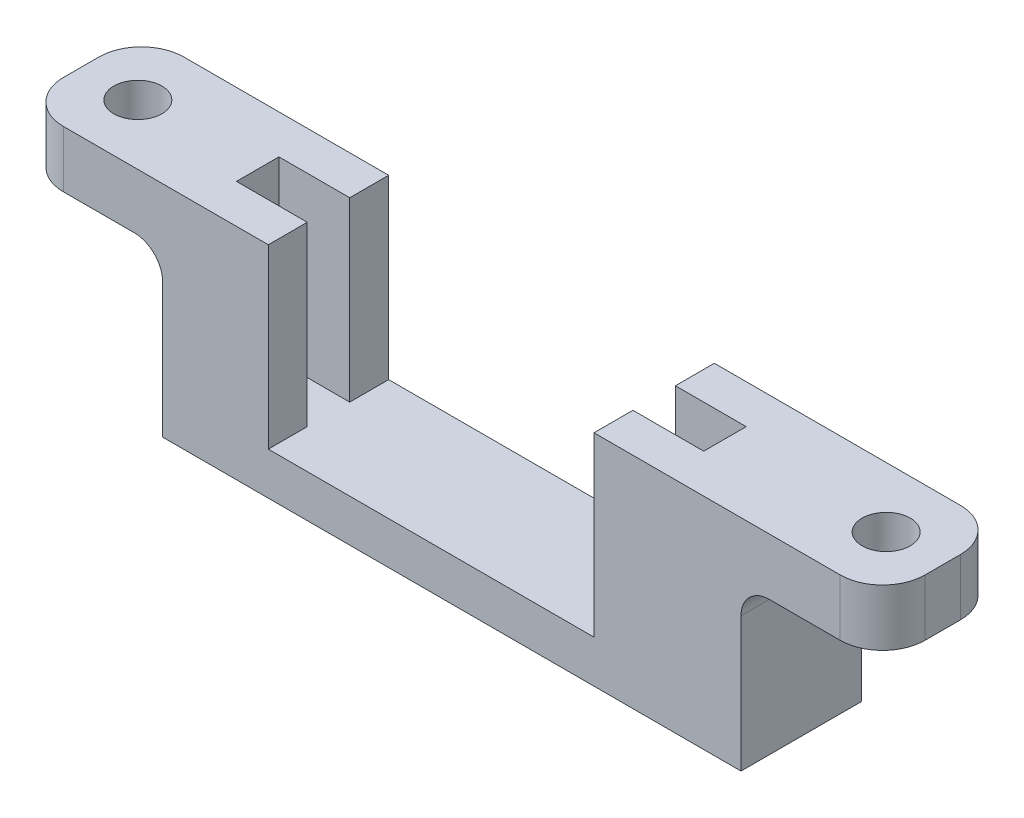
SolidWorks part; units mm, degrees
ref_plane "Front Plane" through (0, 0, 0) normal (0, 0, 1) x (1, 0, 0)
ref_plane "Top Plane" through (0, 0, 0) normal (0, 1, 0) x (1, 0, 0)
ref_plane "Right Plane" through (0, 0, 0) normal (1, 0, 0) x (0, 0, -1)
sketch "Sketch1" plane through (0, 0, 0) normal (0, 1, 0) x (1, 0, 0)
  line L1 (-30.425, 4.25) -> (30.425, 4.25)
  line L2 (-30.425, 4.25) -> (-30.425, -4.25)
  line L3 (-30.425, -4.25) -> (30.425, -4.25)
  line L4 (30.425, 4.25) -> (30.425, -4.25)
  line L5 (-30.425, 4.25) -> (30.425, -4.25) construction
  line L6 (-30.425, -4.25) -> (30.425, 4.25) construction
  point P0 (0, 0)
  dimension "D1" = 8.5
  dimension "D2" = 60.85
extrude "Boss-Extrude1" add sketch "Sketch1" along normal blind 15.5
sketch "Sketch4" plane through (0, 15.5, 0) normal (0, 1, 0) x (1, 0, 0)
  line L0 (-30.425, 0) -> (30.425, 0) construction
  line L1 (30.425, -4.25) -> (30.425, 4.25) construction
  line L2 (-30.425, 4.25) -> (-30.425, -4.25) construction
  line L3 (0, 4.25) -> (0, -4.25) construction
  line L4 (30.425, 4.25) -> (-30.425, 4.25) construction
  line L5 (-30.425, -4.25) -> (30.425, -4.25) construction
  circle A0 centre (-26.425, 0) radius 1.7
  circle A2 centre (26.425, 0) radius 1.7
  point P13 (-30.425, 0)
  dimension "D1" = 3.4
  dimension "D3" = 4
extrude "Cut-Extrude3" cut sketch "Sketch4" against normal through all
sketch "Sketch2" plane through (0, 15.5, 0) normal (0, 1, 0) x (1, 0, 0)
  line L0 (-30.425, 0) -> (30.425, 0) construction
  line L1 (-30.425, 4.25) -> (-30.425, -4.25) construction
  line L2 (30.425, -4.25) -> (30.425, 4.25) construction
  line L3 (-12.96, -4.25) -> (10.04, -4.25)
  line L8 (-12.96, -4.25) -> (-12.96, 4.25)
  line L9 (-12.96, 4.25) -> (10.04, 4.25)
  line L10 (10.04, -4.25) -> (10.04, 4.25)
  line L11 (-12.96, -4.25) -> (10.04, 4.25) construction
  line L12 (-12.96, 4.25) -> (10.04, -4.25) construction
  line L13 (-17.96, -1.5) -> (-12.96, -1.5)
  line L14 (-17.96, -1.5) -> (-17.96, 1.5)
  line L15 (-17.96, 1.5) -> (-12.96, 1.5)
  line L16 (-12.96, -1.5) -> (-12.96, 1.5)
  line L17 (-17.96, -1.5) -> (-12.96, 1.5) construction
  line L18 (-17.96, 1.5) -> (-12.96, -1.5) construction
  line L23 (-1.46, 4.25) -> (-1.46, -4.25) construction
  line L24 (15.04, 1.5) -> (10.04, -1.5) construction
  line L25 (30.425, 4.25) -> (-30.425, 4.25) construction
  line L26 (15.04, -1.5) -> (10.04, 1.5) construction
  line L27 (10.04, -1.5) -> (10.04, 1.5)
  line L28 (15.04, 1.5) -> (10.04, 1.5)
  line L29 (15.04, -1.5) -> (15.04, 1.5)
  line L30 (15.04, -1.5) -> (10.04, -1.5)
  point P2 (-1.46, 0)
  point P10 (-15.46, 0)
  point P23 (12.54, 0)
  dimension "D1" = 1.46
  dimension "D2" = 3
  dimension "D3" = 23
  dimension "D4" = 5
extrude "Cut-Extrude1" cut sketch "Sketch2" against normal blind 12.5
sketch "Sketch3" plane through (0, 0, 0) normal (0, -1, 0) x (1, 0, 0)
  line L0 (30.425, -4.25) -> (-30.425, -4.25) construction
  line L1 (-30.425, 4.25) -> (-20.425, 4.25)
  line L2 (-30.425, 4.25) -> (-30.425, -4.25)
  line L3 (-30.425, -4.25) -> (-20.425, -4.25)
  line L4 (-20.425, 4.25) -> (-20.425, -4.25)
  line L6 (30.425, 4.25) -> (20.425, 4.25)
  line L7 (30.425, 4.25) -> (30.425, -4.25)
  line L8 (30.425, -4.25) -> (20.425, -4.25)
  line L9 (20.425, 4.25) -> (20.425, -4.25)
  dimension "D1" = 10
  dimension "D2" = 10
extrude "Cut-Extrude2" cut sketch "Sketch3" against normal blind 11.5
fillet "Fillet1" radius 2 2 edges at (-20.425, 11.5, 0) (20.425, 11.5, 0)
fillet "Fillet2" radius 3 4 edges at (30.425, 13.5, -4.25) (30.425, 13.5, 4.25) (-30.425, 13.5, -4.25) (-30.425, 13.5, 4.25)
